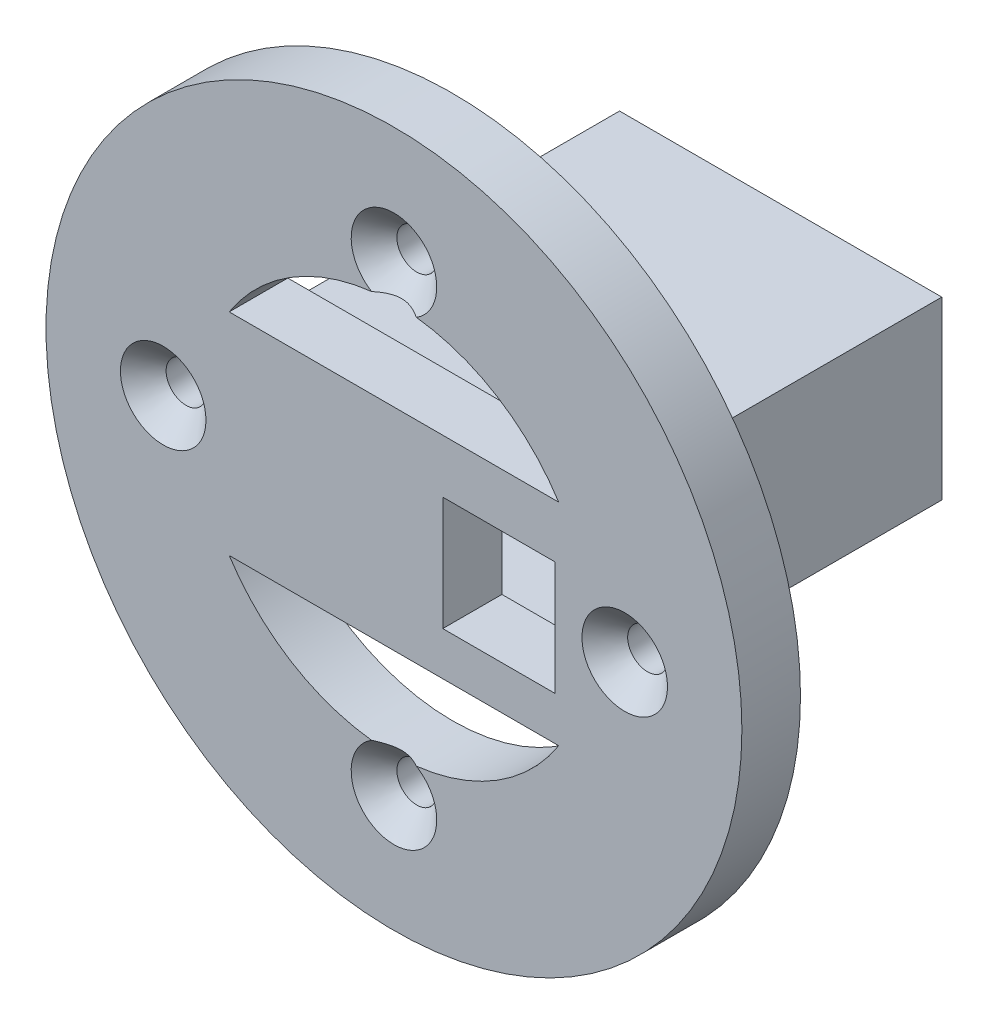
SolidWorks part; units mm, degrees
ref_plane "Front Plane" through (0, 0, 0) normal (0, 0, 1) x (1, 0, 0)
ref_plane "Top Plane" through (0, 0, 0) normal (0, 1, 0) x (1, 0, 0)
ref_plane "Right Plane" through (0, 0, 0) normal (1, 0, 0) x (0, 0, -1)
sketch "Sketch1" plane through (0, 0, 0) normal (0, 0, 1) x (-1, 0, 0)
  line L1 (-14.0585, 9) -> (14.0585, 9)
  line L3 (-14.0585, -9) -> (14.0585, -9)
  line L5 (-14.693, 7.9219) -> (14.693, -7.9219) construction
  line L6 (-14.693, -7.9219) -> (14.693, 7.9219) construction
  circle A0 centre (0, 0) radius 29.6925
  circle A1 centre (0, 0) radius 22.6925
  circle A2 centre (0, 0) radius 16.6925
  circle A3 centre (0, 0) radius 19.6925
  point P5 (0, 16.6925)
  point P7 (16.6925, 0)
  point P9 (0, -16.6925)
  point P11 (-16.6925, 0)
  dimension "D1" = 6
  dimension "D2" = 45.3851
  dimension "D3" = 3
  dimension "D4" = 7
  dimension "D5" = 33.3851
  dimension "D7" = 59.3851
  dimension "D6" = 18
extrude "Boss-Extrude1" add sketch "Sketch1" along normal blind 5 contours L3 A2 L1 | A3 A2 | A1 A3 | A0 A1
sketch "Sketch4" plane through (0, 0, 0) normal (0, 0, 1) x (-1, 0, 0)
  line L1 (-14.0585, 10.3647) -> (14.0585, 10.3647)
  line L3 (-14.0585, -7.6353) -> (14.0585, -7.6353)
  line L5 (-14.693, 7.9219) -> (14.693, -7.9219) construction
  line L6 (-14.693, -7.9219) -> (14.693, 7.9219) construction
  circle A0 centre (0, 0) radius 29.6925
  circle A1 centre (0, 0) radius 22.6925
  circle A3 centre (0, 0) radius 19.6925
  point P22 (0, 19.6925)
  point P24 (0, -19.6925)
  point P26 (19.6925, 0)
  point P28 (-19.6925, 0)
  dimension "D2" = 45.3851
  dimension "D3" = 3
  dimension "D4" = 7
  dimension "D6" = 18
hole_wizard "CSK for M3 Flat Head Machine Screw2" positions "Sketch7" profile "Sketch8" countersink size "M3" standard "ANSI Metric"
sketch "Sketch7" plane through (0, 0, 5) normal (0, 0, 1) x (1, 0, 0)
  point P0 (0, 19.6925)
  point P3 (0, -19.6925)
  point P6 (19.6925, 0)
  point P9 (-19.6925, 0)
sketch "Sketch8" plane through (0, 19.6925, 5) normal (1, 0, 0) x (0, -1, 0)
  line L0 (0, 0) -> (0, 13.0215)
  line L1 (0, 13.0215) -> (1.7, 12)
  line L2 (1.7, 12) -> (1.7, 1.95)
  line L3 (1.7, 1.95) -> (3.65, 0)
  line L5 (3.65, 0) -> (0, 0)
  line L6 (-1.7, 1.95) -> (-3.65, 0) construction
  line L10 (0, 13.0215) -> (-1.7, 12) construction
  line L11 (0, -6.35) -> (0, 107.95) construction
  dimension "Hole Dia." = 3.4
  dimension "Hole Depth" = 12
  dimension "Near C'Sink Dia." = 7.3
  dimension "Near C'Sink Angle" = 90
  dimension "Drill Angle" = 118
sketch "Sketch9" plane through (0, 0, 0) normal (0, 1, 0) x (1, 0, 0)
  line L1 (-13.75, 0) -> (13.75, 0)
  line L7 (14.693, 0) -> (-14.693, 0) construction
  line L8 (-13.75, 28) -> (13.75, 0) construction
  line L9 (-13.75, 0) -> (13.75, 28) construction
  line L10 (13.75, 0) -> (13.75, 28)
  line L11 (-13.75, 28) -> (13.75, 28)
  line L12 (-13.75, 0) -> (-13.75, 28)
  point P0 (0, 14)
  point P18 (0, 8.5)
  dimension "D1" = 27.5
  dimension "D2" = 28
  dimension "D3" = 28
extrude "Boss-Extrude2" add sketch "Sketch9" along normal mid plane 15
sketch "Sketch10" plane through (0, 0, 0) normal (0, 1, 0) x (1, 0, 0)
  line L0 (-13.75, 28) -> (13.75, 28)
  line L1 (-13.75, 28) -> (-13.75, 0.1022)
  line L2 (13.75, 28) -> (13.75, 0.1022)
  line L3 (-13.75, 0.1022) -> (13.75, 0.1022)
  line L4 (-13.75, 28) -> (13.75, 0.1022) construction
  line L5 (-13.75, 0.1022) -> (13.75, 28) construction
  line L6 (-11.75, 0.05) -> (11.75, 0.05)
  line L7 (-11.75, 0.05) -> (-11.75, 25.5)
  line L8 (11.75, 0.05) -> (11.75, 25.5)
  line L9 (-11.75, 25.5) -> (11.75, 25.5)
  point P0 (0, 0.05)
  dimension "D1" = 25.45
  dimension "D2" = 23.5
  dimension "D3" = 2.5
sketch "Sketch11" plane through (0, 0, 5) normal (0, 0, 1) x (1, 0, 0)
  line L0 (13.75, -5.2927) -> (13.75, 4.425)
  line L5 (13.75, -5.2927) -> (4.1647, -5.2927)
  line L6 (13.75, 4.425) -> (4.1647, 4.425)
  line L7 (4.1647, -5.2927) -> (4.1647, 4.425)
  line L8 (13.75, 7.5) -> (13.75, -7.5) construction
extrude "Cut-Extrude1" cut sketch "Sketch10" against normal mid plane 12.2 contours L8 L9 L7 L6
sketch "Sketch12" plane through (0, 0, -28) normal (0, 0, 1) x (1, 0, 0)
  line L0 (13.75, 7.5) -> (13.75, -7.5) construction
  line L1 (5.75, 5.5) -> (11.75, 5.5)
  line L2 (5.75, 5.5) -> (5.75, -5.5)
  line L3 (5.75, -5.5) -> (11.75, -5.5)
  line L4 (11.75, 5.5) -> (11.75, -5.5)
  line L5 (5.75, 5.5) -> (11.75, -5.5) construction
  line L6 (5.75, -5.5) -> (11.75, 5.5) construction
  line L7 (13.75, 7.5) -> (-13.75, 7.5) construction
  line L8 (13.75, -7.5) -> (-13.75, -7.5) construction
  point P0 (0, 0)
  point P5 (0, 0)
  dimension "D1" = 2
  dimension "D2" = 2
  dimension "18.5" = 6
  dimension "D3" = 2
extrude "Cut-Extrude2" cut sketch "Sketch12" along normal blind 3 contours L3 L4 L1 L2
extrude "Cut-Extrude3" cut sketch "Sketch11" against normal up to surface (5.05 mm away) contours L6 L7 L5 L0 up to face at (0, 0, -0.05)
